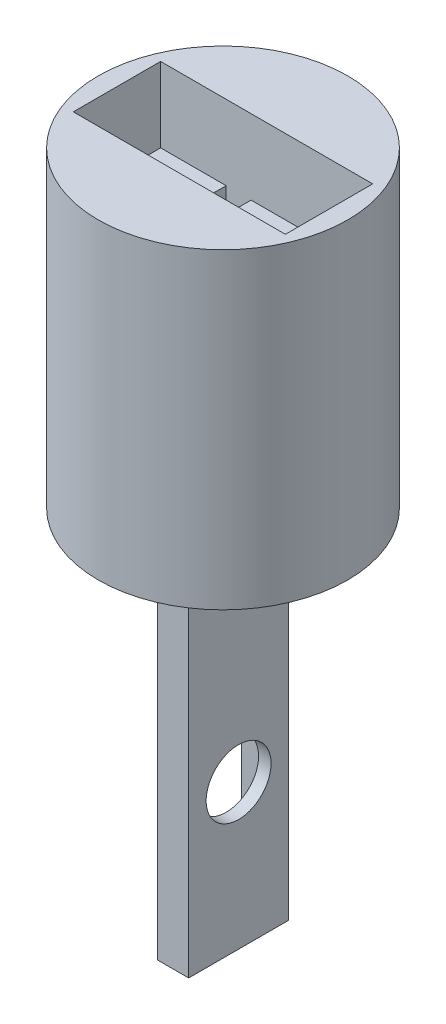
SolidWorks part; units mm, degrees
ref_plane "Front Plane" through (0, 0, 0) normal (0, 0, 1) x (1, 0, 0)
ref_plane "Top Plane" through (0, 0, 0) normal (0, 1, 0) x (1, 0, 0)
ref_plane "Right Plane" through (0, 0, 0) normal (1, 0, 0) x (0, 0, -1)
sketch "Sketch3" plane through (0, 0, 0) normal (0, 1, 0) x (1, 0, 0)
  circle A0 centre (0, 0) radius 10
  dimension "D1" = 20
extrude "Boss-Extrude1" add sketch "Sketch3" along normal blind 25
sketch "Sketch4" plane through (0, 0, 0) normal (0, -1, 0) x (-1, 0, 0)
  line L1 (1.25, 4) -> (-1.25, 4)
  line L2 (1.25, 4) -> (1.25, -4)
  line L3 (1.25, -4) -> (-1.25, -4)
  line L4 (-1.25, 4) -> (-1.25, -4)
  line L5 (1.25, 4) -> (-1.25, -4) construction
  line L6 (1.25, -4) -> (-1.25, 4) construction
  point P0 (0, 0)
  dimension "D1" = 2.5
  dimension "D2" = 8
  dimension "D3" = 0
extrude "Boss-Extrude2" add sketch "Sketch4" along normal blind 30
sketch "Sketch5" plane through (1.25, 0, 0) normal (1, 0, 0) x (0, 0, -1)
  line L1 (4, 0) -> (-4, 0) construction
  circle A0 centre (0, -18.4) radius 2.6
  dimension "D1" = 5.2
  dimension "D2" = 18.4
extrude "Cut-Extrude1" cut sketch "Sketch5" against normal up to next
sketch "Sketch6" plane through (-1.25, 0, 0) normal (-1, 0, 0) x (0, 0, 1)
  line L1 (-2.75, -29) -> (2.75, -29)
  line L2 (-2.75, -29) -> (-2.75, -7.8)
  line L3 (-2.75, -7.8) -> (2.75, -7.8)
  line L4 (2.75, -29) -> (2.75, -7.8)
  line L5 (-2.75, -29) -> (2.75, -7.8) construction
  line L6 (-2.75, -7.8) -> (2.75, -29) construction
  point P0 (0, -18.4)
  dimension "D1" = 21.2
  dimension "D2" = 5.5
extrude "Cut-Extrude2" cut sketch "Sketch6" against normal blind 1.5
sketch "Sketch7" plane through (0, 25, 0) normal (0, 1, 0) x (1, 0, 0)
  line L0 (-10, 0) -> (10, 0) construction
  line L1 (-8.5, -3.5) -> (8.5, -3.5)
  line L2 (-8.5, -3.5) -> (-8.5, 3.5)
  line L3 (-8.5, 3.5) -> (8.5, 3.5)
  line L4 (8.5, -3.5) -> (8.5, 3.5)
  circle A0 centre (0, 0) radius 10 construction
  point P4 (-8.5, 0)
  dimension "D1" = 7
  dimension "D2" = 17
  dimension "D3" = 1.5
extrude "Cut-Extrude3" cut sketch "Sketch7" against normal blind 6
sketch "Sketch8" plane through (0, 19, 0) normal (0, 1, 0) x (1, 0, 0)
  line L0 (8.5, 0) -> (-1.25, 0) construction
  line L1 (8.5, -3.5) -> (8.5, 3.5) construction
  line L2 (8.5, 3.5) -> (-8.5, 3.5) construction
  line L3 (-1.25, 3.5) -> (-3.25, 3.5)
  line L4 (-1.25, 3.5) -> (-1.25, -3.5)
  line L5 (-1.25, -3.5) -> (-3.25, -3.5)
  line L6 (-3.25, 3.5) -> (-3.25, -3.5)
  line L7 (-8.5, 3.5) -> (-8.5, -3.5) construction
  dimension "D1" = 9.75
  dimension "D2" = 2
extrude "Cut-Extrude4" cut sketch "Sketch8" against normal blind 4
